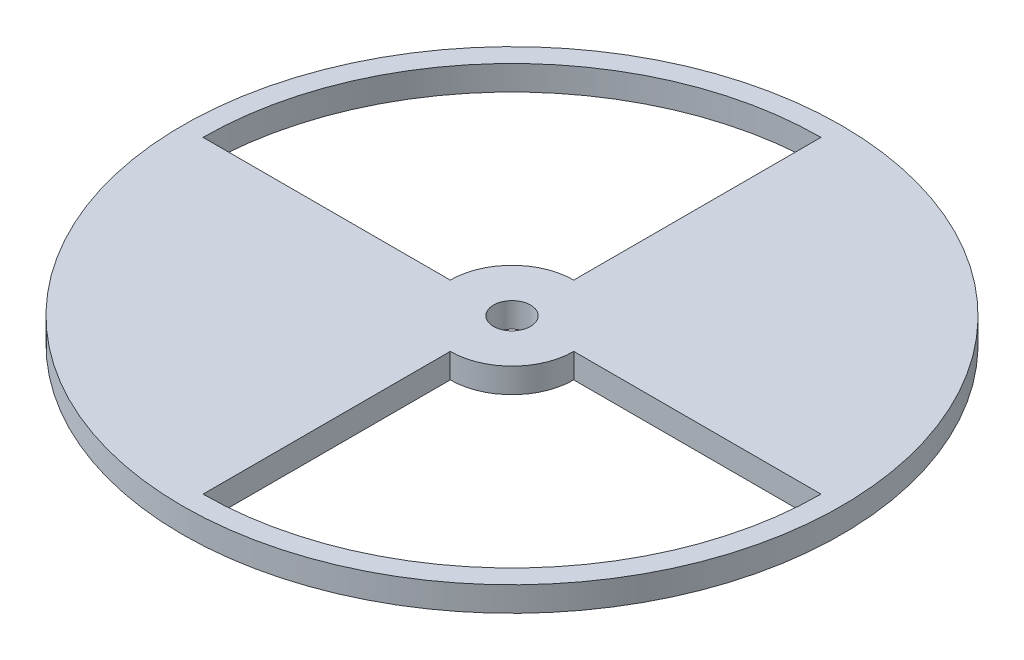
SolidWorks part; units mm, degrees
ref_plane "前视基准面" through (0, 0, 0) normal (0, 0, 1) x (1, 0, 0)
ref_plane "上视基准面" through (0, 0, 0) normal (0, 1, 0) x (1, 0, 0)
ref_plane "右视基准面" through (0, 0, 0) normal (1, 0, 0) x (0, 0, -1)
sketch "草图1" plane through (0, 0, 0) normal (0, 1, 0) x (1, 0, 0)
  circle A0 centre (0, 0) radius 40
  circle A1 centre (0, 0) radius 2.25
  dimension "D1" = 80
  dimension "D2" = 4.5
extrude "凸台-拉伸1" add sketch "草图1" along normal blind 3
sketch "草图2" plane through (0, 3, 0) normal (0, 1, 0) x (1, 0, 0)
  line L0 (0, 7.5) -> (0, 37.5) construction
  line L1 (-37.5, 0) -> (-7.5, 0)
  line L2 (0, 37.5) -> (0, 7.5)
  line L3 (7.5, 0) -> (37.5, 0)
  line L4 (0, -7.5) -> (0, -37.5)
  arc A0 (0, -7.5) -> (7.5, 0) centre (0, 0) ccw
  arc A1 (0, 37.5) -> (-37.5, 0) centre (0, 0) ccw
  arc A3 (0, -37.5) -> (37.5, 0) centre (0, 0) ccw
  arc A4 (0, 7.5) -> (-7.5, 0) centre (0, 0) ccw
  dimension "D1" = 15
  dimension "D2" = 30
extrude "切除-拉伸1" cut sketch "草图2" against normal up to next
